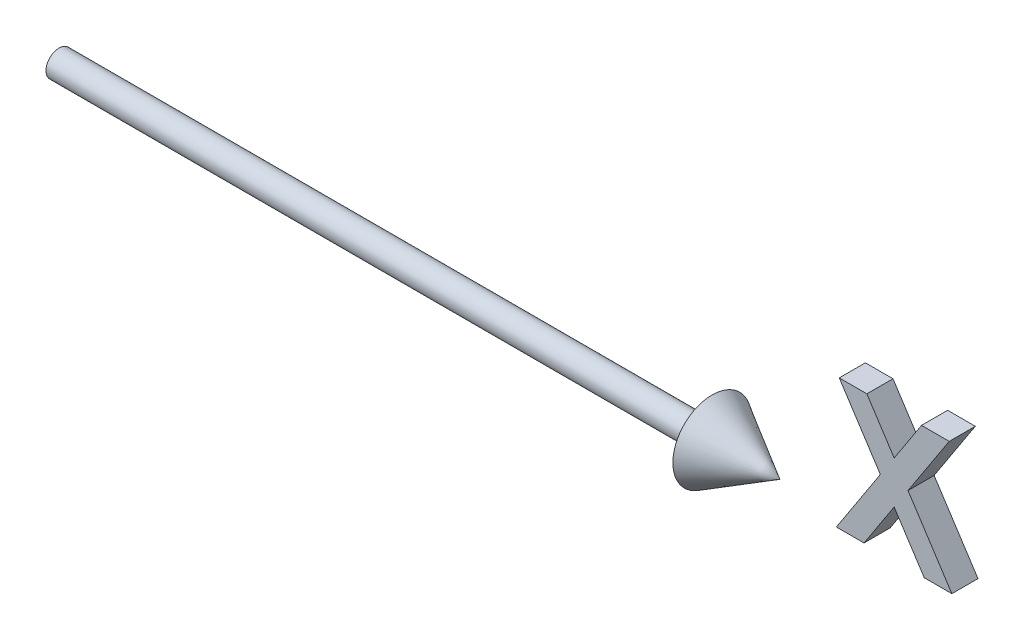
SolidWorks part; units mm, degrees
ref_plane "Front Plane" through (0, 0, 0) normal (0, 0, 1) x (1, 0, 0)
ref_plane "Top Plane" through (0, 0, 0) normal (0, 1, 0) x (1, 0, 0)
ref_plane "Right Plane" through (0, 0, 0) normal (1, 0, 0) x (0, 0, -1)
sketch "Sketch1" plane through (0, 0, 0) normal (1, 0, 0) x (0, 0, -1)
  circle A0 centre (0, 0) radius 1
  dimension "D1" = 2
extrude "Boss-Extrude1" add sketch "Sketch1" along normal blind 50
sketch "Sketch4" plane through (0, 0, 0) normal (0, 1, 0) x (1, 0, 0)
  line L0 (50, 0) -> (50, 3)
  line L1 (50, -1) -> (50, 1) construction
  line L2 (50, 3) -> (55.1962, 0)
  line L3 (50, 0) -> (55.1962, 0)
  dimension "D1" = 3
  dimension "D2" = 60
revolve "Revolve1" add sketch "Sketch4" angle 360 about L3
sketch "Sketch5" plane through (0, 0, 0) normal (0, 0, 1) x (1, 0, 0)
  line L0 (60.1962, 0) -> (78.3322, 0) construction
  line L2 (55.1962, 0) -> (55.1962, 8.5945) construction
  text T0 "<b>X</b>" font "Century Gothic" height 10
  dimension "D1" = 5
extrude "Boss-Extrude2" add sketch "Sketch5" along normal mid plane 2 separate body
